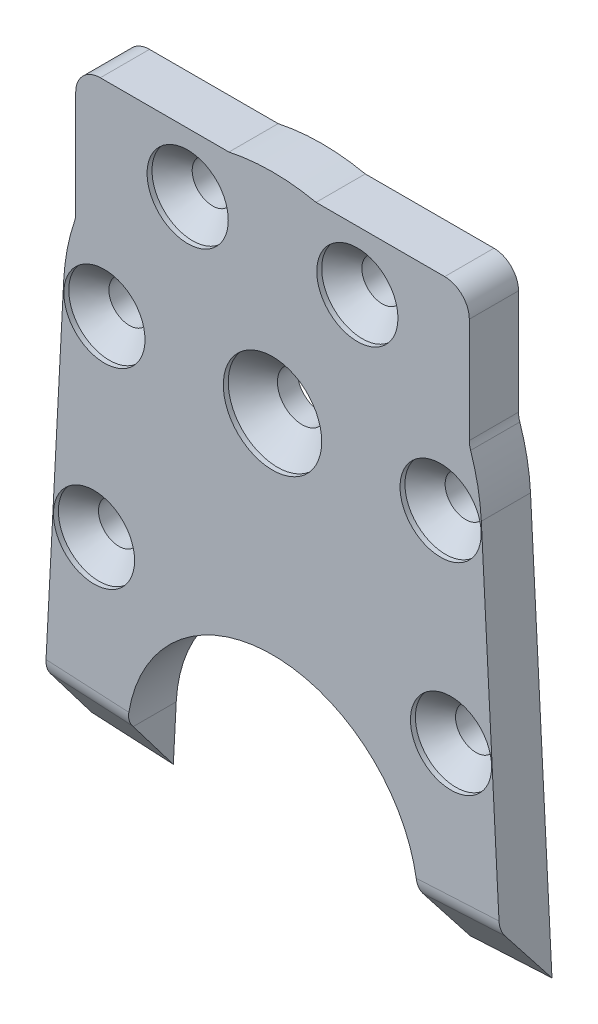
SolidWorks part; units mm, degrees
ref_plane "Front Plane" through (0, 0, 0) normal (0, 0, 1) x (1, 0, 0)
ref_plane "Top Plane" through (0, 0, 0) normal (0, 1, 0) x (1, 0, 0)
ref_plane "Right Plane" through (0, 0, 0) normal (1, 0, 0) x (0, 0, -1)
sketch "Sketch1" plane through (0, 0, 0) normal (0, 0, 1) x (1, 0, 0)
  line L0 (12, 4.5621) -> (12, 10.9702) construction
  line L1 (10.5, 12.4702) -> (4.0797, 12.4702) construction
  line L2 (2.5818, 11.0487) -> (2.4454, 8.4459) construction
  line L3 (7.7394, 0.4056) -> (9.0478, -24.5601) construction
  line L5 (14.0409, -24.2985) -> (12.7325, 0.6673) construction
  line L6 (-2.4454, 8.4459) -> (-2.5818, 11.0487) construction
  line L7 (-4.0797, 12.4702) -> (-10.5, 12.4702) construction
  line L8 (-12, 10.9702) -> (-12, 4.5621) construction
  line L9 (-12.7325, 0.6673) -> (-14.0409, -24.2985) construction
  line L11 (-9.0478, -24.5601) -> (-7.7394, 0.4056) construction
  line L12 (12, 4.5621) -> (12, 10.9702)
  line L13 (10.5, 12.4702) -> (4.0797, 12.4702)
  line L14 (2.5818, 11.0487) -> (2.4454, 8.4459)
  line L15 (7.7394, 0.4056) -> (9.0478, -24.5601)
  line L16 (9.0478, -24.5601) -> (14.0409, -24.2985)
  line L17 (14.0409, -24.2985) -> (12.7325, 0.6673)
  line L18 (-2.4454, 8.4459) -> (-2.5818, 11.0487)
  line L19 (-4.0797, 12.4702) -> (-10.5, 12.4702)
  line L20 (-12, 10.9702) -> (-12, 4.5621)
  line L21 (-12.7325, 0.6673) -> (-14.0409, -24.2985)
  line L22 (-14.0409, -24.2985) -> (-9.0478, -24.5601)
  line L23 (-9.0478, -24.5601) -> (-7.7394, 0.4056)
  line L34 (10.5, 12.4702) -> (2.6563, 12.4702)
  line L35 (12, 4.5621) -> (12, 10.9702)
  line L36 (14.0031, -23.5759) -> (12.7325, 0.6673)
  line L37 (-12.7325, 0.6673) -> (-13.1774, -7.8211)
  line L38 (-12.7325, 0.6673) -> (-13.1774, -7.8211)
  line L42 (-12, 10.9702) -> (-12, 4.5621)
  line L43 (-2.6563, 12.4702) -> (-10.5, 12.4702)
  line L44 (10.5, 12.4702) -> (2.6563, 12.4702)
  line L45 (12, 4.5621) -> (12, 10.9702)
  line L46 (14.0031, -23.5759) -> (12.7325, 0.6673)
  line L52 (-12, 10.9702) -> (-12, 4.5621)
  line L53 (-2.6563, 12.4702) -> (-10.5, 12.4702)
  line L96 (9.0099, -23.8376) -> (14.0031, -23.5759)
  line L97 (9.0099, -23.8376) -> (14.0031, -23.5759)
  line L98 (8.87, -21.1673) -> (9.0099, -23.8376)
  line L99 (8.87, -21.1673) -> (9.0099, -23.8376)
  line L100 (-9.0099, -23.8376) -> (-8.87, -21.1673)
  line L101 (-9.0099, -23.8376) -> (-8.87, -21.1673)
  line L102 (-14.0031, -23.5759) -> (-9.0099, -23.8376)
  line L103 (-14.0031, -23.5759) -> (-9.0099, -23.8376)
  line L104 (-13.7531, -18.806) -> (-14.0031, -23.5759)
  line L105 (-13.7531, -18.806) -> (-14.0031, -23.5759)
  line L106 (-18.9174, -17.0333) -> (-15.1725, -17.2295)
  line L107 (-18.9174, -17.0333) -> (-15.1725, -17.2295)
  line L108 (-18.4987, -9.0442) -> (-18.9174, -17.0333)
  line L109 (-18.4987, -9.0442) -> (-18.9174, -17.0333)
  line L110 (-14.7538, -9.2405) -> (-18.4987, -9.0442)
  line L111 (-14.7538, -9.2405) -> (-18.4987, -9.0442)
  arc A0 (12, 10.9702) -> (10.5, 12.4702) centre (10.5, 10.9702) ccw construction
  arc A1 (4.0797, 12.4702) -> (2.5818, 11.0487) centre (4.0797, 10.9702) ccw construction
  arc A2 (2.4454, 8.4459) -> (3.3039, 7.0105) centre (3.9433, 8.3674) ccw construction
  arc A3 (7.7394, 0.4056) -> (3.3039, 7.0105) centre (0, 0) ccw construction
  arc A4 (12.7325, 0.6673) -> (12.0789, 4.0819) centre (0, 0) ccw construction
  arc A5 (12, 4.5621) -> (12.0789, 4.0819) centre (13.5, 4.5621) ccw construction
  arc A6 (-2.5818, 11.0487) -> (-4.0797, 12.4702) centre (-4.0797, 10.9702) ccw construction
  arc A7 (-10.5, 12.4702) -> (-12, 10.9702) centre (-10.5, 10.9702) ccw construction
  arc A8 (-12.0789, 4.0819) -> (-12, 4.5621) centre (-13.5, 4.5621) ccw construction
  arc A9 (-12.0789, 4.0819) -> (-12.7325, 0.6673) centre (0, 0) ccw construction
  arc A10 (-3.3039, 7.0105) -> (-7.7394, 0.4056) centre (0, 0) ccw construction
  arc A11 (-3.3039, 7.0105) -> (-2.4454, 8.4459) centre (-3.9433, 8.3674) ccw construction
  arc A12 (12, 10.9702) -> (10.5, 12.4702) centre (10.5, 10.9702) ccw
  arc A13 (4.0797, 12.4702) -> (2.5818, 11.0487) centre (4.0797, 10.9702) ccw
  arc A14 (2.4454, 8.4459) -> (3.3039, 7.0105) centre (3.9433, 8.3674) ccw
  arc A15 (7.7394, 0.4056) -> (3.3039, 7.0105) centre (0, 0) ccw
  arc A16 (12.7325, 0.6673) -> (12.0789, 4.0819) centre (0, 0) ccw
  arc A17 (12, 4.5621) -> (12.0789, 4.0819) centre (13.5, 4.5621) ccw
  arc A18 (-2.5818, 11.0487) -> (-4.0797, 12.4702) centre (-4.0797, 10.9702) ccw
  arc A19 (-10.5, 12.4702) -> (-12, 10.9702) centre (-10.5, 10.9702) ccw
  arc A20 (-12.0789, 4.0819) -> (-12, 4.5621) centre (-13.5, 4.5621) ccw
  arc A21 (-12.0789, 4.0819) -> (-12.7325, 0.6673) centre (0, 0) ccw
  arc A22 (-3.3039, 7.0105) -> (-7.7394, 0.4056) centre (0, 0) ccw
  arc A23 (-3.3039, 7.0105) -> (-2.4454, 8.4459) centre (-3.9433, 8.3674) ccw
  circle A24 centre (10.25, 0) radius 1.05 construction
  circle A25 centre (5.1729, 8.8489) radius 1.05 construction
  circle A26 centre (-5.1729, 8.8489) radius 1.05 construction
  circle A27 centre (-10.25, 0) radius 1.05 construction
  circle A28 centre (10.25, 0) radius 1.05
  circle A29 centre (5.1729, 8.8489) radius 1.05
  circle A30 centre (-5.1729, 8.8489) radius 1.05
  circle A31 centre (-10.25, 0) radius 1.05
  circle A32 centre (0, 0) radius 12.75
  circle A33 centre (0, 0) radius 1.5
  circle A34 centre (-5.1729, 8.8489) radius 1.25
  circle A35 centre (-10.25, 0) radius 1.25
  circle A36 centre (5.1729, 8.8489) radius 1.25
  circle A37 centre (10.25, 0) radius 1.25
  arc A46 (12, 10.9702) -> (10.5, 12.4702) centre (10.5, 10.9702) ccw
  arc A47 (12, 4.5621) -> (12.0789, 4.0819) centre (13.5, 4.5621) ccw
  arc A48 (12.7325, 0.6673) -> (12.0789, 4.0819) centre (0, 0) ccw
  arc A49 (8.87, -21.1673) -> (-8.87, -21.1673) centre (0, -21.6321) ccw
  arc A50 (-12.0789, 4.0819) -> (-12.7325, 0.6673) centre (0, 0) ccw
  arc A51 (-12.0789, 4.0819) -> (-12, 4.5621) centre (-13.5, 4.5621) ccw
  arc A52 (-10.5, 12.4702) -> (-12, 10.9702) centre (-10.5, 10.9702) ccw
  arc A53 (2.6563, 12.4702) -> (-2.6563, 12.4702) centre (0, 0) ccw
  arc A54 (12, 10.9702) -> (10.5, 12.4702) centre (10.5, 10.9702) ccw
  arc A55 (12, 4.5621) -> (12.0789, 4.0819) centre (13.5, 4.5621) ccw
  arc A56 (12.7325, 0.6673) -> (12.0789, 4.0819) centre (0, 0) ccw
  arc A57 (8.87, -21.1673) -> (-8.87, -21.1673) centre (0, -21.6321) ccw
  arc A58 (-12.0789, 4.0819) -> (-12.7325, 0.6673) centre (0, 0) ccw
  arc A59 (-12.0789, 4.0819) -> (-12, 4.5621) centre (-13.5, 4.5621) ccw
  arc A60 (-10.5, 12.4702) -> (-12, 10.9702) centre (-10.5, 10.9702) ccw
  arc A61 (2.6563, 12.4702) -> (-2.6563, 12.4702) centre (0, 0) ccw
  circle A70 centre (-10.8849, -11.9832) radius 1.05 construction
  circle A71 centre (-10.8849, -11.9832) radius 1.05
  circle A72 centre (10.8849, -11.9832) radius 1.05 construction
  circle A73 centre (10.8849, -11.9832) radius 1.05
  circle A74 centre (-10.8849, -11.9832) radius 1.25
  circle A75 centre (10.8849, -11.9832) radius 1.25
  arc A120 (-13.7531, -18.806) -> (-15.1725, -17.2295) centre (-15.251, -18.7275) ccw
  arc A121 (-13.7531, -18.806) -> (-15.1725, -17.2295) centre (-15.251, -18.7275) ccw
  arc A122 (-14.7538, -9.2405) -> (-13.1774, -7.8211) centre (-14.6753, -7.7426) ccw
  arc A123 (-14.7538, -9.2405) -> (-13.1774, -7.8211) centre (-14.6753, -7.7426) ccw
  dimension "D1" = 3
  dimension "D2" = 2.5
  dimension "D3" = 0
extrude "Boss-Extrude1" add sketch "Sketch1" along normal blind 3
hole_wizard "CSK for M3 Flat Head Machine Screw1" positions "Sketch2" profile "Sketch3" countersink size "M3" standard "ANSI Metric"
sketch "Sketch2" plane through (0, 0, 3) normal (0, 0, 1) x (1, 0, 0)
  point P0 (0, 0)
sketch "Sketch3" plane through (0, 0, 3) normal (1, 0, 0) x (0, -1, 0)
  line L0 (0, 0) -> (0, 5.9013)
  line L1 (0, 5.9013) -> (1.5, 5)
  line L2 (1.5, 5) -> (1.5, 1.8)
  line L3 (1.5, 1.8) -> (3, 0.3)
  line L4 (3, 0.3) -> (3, 0)
  line L6 (3, 0) -> (0, 0)
  line L7 (-1.5, 1.8) -> (-3, 0.3) construction
  line L10 (0, 5.9013) -> (-1.5, 5) construction
  line L11 (0, -6.35) -> (0, 107.95) construction
  dimension "Hole Dia." = 3
  dimension "Hole Depth" = 5
  dimension "C'Sink Dia." = 6
  dimension "C'Sink Angle" = 90
  dimension "Drill Angle" = 118
  dimension "Head Clearance" = 0.3
hole_wizard "CSK for M2.5 Flat Head Machine Screw2" positions "Sketch4" profile "Sketch6" countersink size "M2.5" standard "ANSI Metric"
sketch "Sketch4" plane through (0, 0, 3) normal (0, 0, 1) x (1, 0, 0)
  point P0 (-10.25, 0)
  point P4 (-5.1729, 8.8489)
  point P7 (5.1729, 8.8489)
  point P10 (10.25, 0)
  point P15 (-10.8849, -11.9832)
  point P18 (10.8849, -11.9832)
sketch "Sketch6" plane through (-10.25, 0, 3) normal (1, 0, 0) x (0, -1, 0)
  line L0 (0, 0) -> (0, 5.7511)
  line L1 (0, 5.7511) -> (1.25, 5)
  line L2 (1.25, 5) -> (1.25, 1.525)
  line L3 (1.25, 1.525) -> (2.475, 0.3)
  line L4 (2.475, 0.3) -> (2.475, 0)
  line L6 (2.475, 0) -> (0, 0)
  line L7 (-1.25, 1.525) -> (-2.475, 0.3) construction
  line L10 (0, 5.7511) -> (-1.25, 5) construction
  line L11 (0, -6.35) -> (0, 107.95) construction
  dimension "Hole Dia." = 2.5
  dimension "Hole Depth" = 5
  dimension "C'Sink Dia." = 4.95
  dimension "C'Sink Angle" = 90
  dimension "Drill Angle" = 118
  dimension "Head Clearance" = 0.3
sketch "Sketch10" plane through (12.7325, 0.6673, 0) normal (0.9986, 0.0523, 0) x (0, 0, -1)
  line L0 (0, -25) -> (-3, -21.1132)
  line L1 (-3, -25) -> (-3, 0) construction
  line L2 (0, -25) -> (4.4377, -30.7495) construction
  line L7 (0, -25) -> (0, 0)
  line L8 (0, 0) -> (-3, 0)
  line L9 (-3, 0) -> (-3, -25)
  line L10 (-3, -25) -> (0, -25)
  line L11 (0, -25) -> (0, 0)
  line L12 (0, 0) -> (-3, 0)
  line L13 (-3, 0) -> (-3, -25)
  line L14 (-3, -25) -> (0, -25)
  line M8 (-3, 0) -> (-3, -25)
  line M9 (-3, -25) -> (0, -25)
  dimension "D1" = 0
extrude "Cut-Extrude4" cut sketch "Sketch10" against normal up to next contours L0 M9 M8
sketch "Sketch11" plane through (-12.7325, 0.6673, 0) normal (-0.9986, 0.0523, 0) x (0, 0, 1)
  line L0 (0, -25) -> (3, -21.1132)
  line L1 (3, 0) -> (3, -25) construction
  line L2 (0, -25) -> (-4.4377, -30.7495) construction
  line L7 (0, 0) -> (0, -25)
  line L8 (0, -25) -> (3, -25)
  line L9 (3, -25) -> (3, 0)
  line L10 (3, 0) -> (0, 0)
  line L11 (0, 0) -> (0, -25)
  line L12 (0, -25) -> (3, -25)
  line L13 (3, -25) -> (3, 0)
  line L16 (3, 0) -> (0, 0)
  line M7 (0, -25) -> (3, -25)
  line M8 (3, -25) -> (3, 0)
  dimension "D1" = 0
extrude "Cut-Extrude5" cut sketch "Sketch11" against normal up to next contours L0 M7 M8
fillet "Fillet2" radius 1.5 2 edges at (11.3342, -20.5481, 3) (-11.3342, -20.5481, 3)
